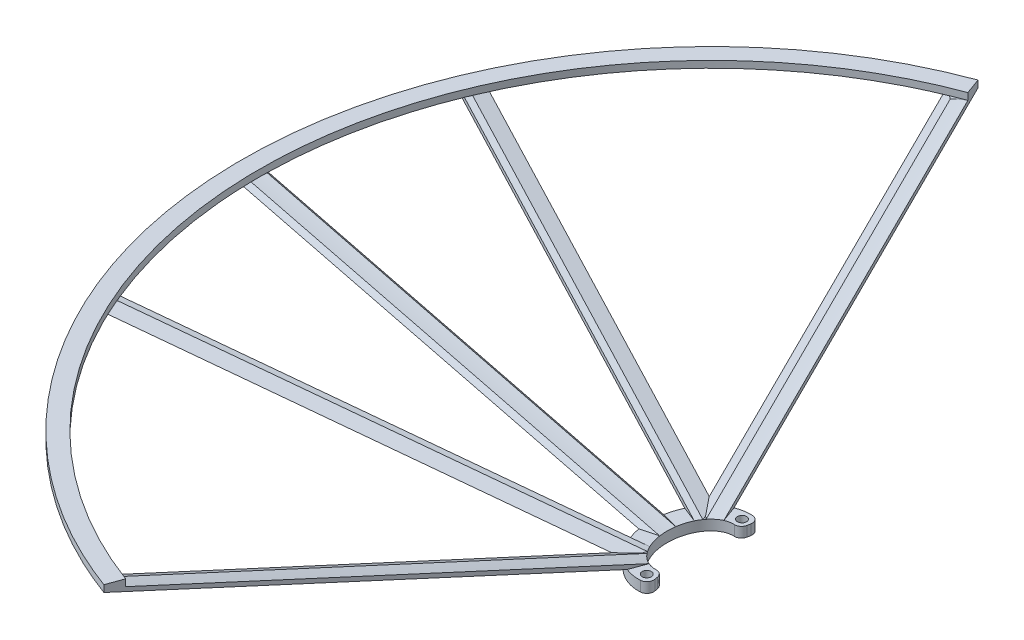
SolidWorks part; units mm, degrees
ref_plane "Front Plane" through (0, 0, 0) normal (0, 0, 1) x (1, 0, 0)
ref_plane "Top Plane" through (0, 0, 0) normal (0, 1, 0) x (1, 0, 0)
ref_plane "Right Plane" through (0, 0, 0) normal (1, 0, 0) x (0, 0, -1)
sketch "Sketch1" plane through (0, 0, 0) normal (0, 1, 0) x (1, 0, 0)
  line L0 (1.9656, -11.1475) -> (2.8392, -16.1017)
  line L1 (1.9656, 11.1475) -> (2.8392, 16.1017)
  line L2 (0, 16.5) -> (0, -16.5) construction
  line L3 (0, 0) -> (2.8392, 16.1017) construction
  line L4 (0, 0) -> (2.8392, -16.1017) construction
  line L5 (-8, 0) -> (8, 0) construction
  ellipse E0 centre (0, 0) end of major axis (0, 11.5) minor radius 8 (1.9656, 11.1475) -> (1.9656, -11.1475) ccw
  ellipse E1 centre (0, 0) end of major axis (0, 16.5) minor radius 13 (2.8392, 16.1017) -> (2.8392, -16.1017) ccw
  dimension "D1" = 8
  dimension "D2" = 5
  dimension "D3" = 10
  dimension "D4" = 10
  dimension "D5" = 5
  dimension "D6" = 23
extrude "Boss-Extrude1" add sketch "Sketch1" along normal blind 3
sketch "Sketch2" plane through (0, 3, 0) normal (0, 1, 0) x (1, 0, 0)
  line L0 (0, -11.5) -> (0, -16.5) construction
  circle A1 centre (0, -14) radius 1.35
  ellipse E1 centre (0, 0) end of major axis (0, 11.5) minor radius 8 (1.9656, 11.1475) -> (1.9656, -11.1475) ccw construction
  ellipse E2 centre (0, 0) end of major axis (0, 16.5) minor radius 13 (2.8392, 16.1017) -> (2.8392, -16.1017) ccw construction
  dimension "D1" = 2.7
extrude "Cut-Extrude1" cut sketch "Sketch2" against normal up to next
mirror "Mirror1" about plane through (0, 0, 0) normal (0, 0, 1) of "Cut-Extrude1"
fillet "Fillet1" radius 2 4 edges at (2.8392, 1.5, 16.1017) (1.9656, 1.5, 11.1475) (1.9656, 1.5, -11.1475) (2.8392, 1.5, -16.1017)
sketch "Sketch4" plane through (0, 3, 0) normal (0, 1, 0) x (1, 0, 0)
  line L0 (-9.0377, -11.8603) -> (-5.2477, -8.6801)
  line L1 (-4.047, -15.6801) -> (-2.3421, -10.9961)
  line L2 (0, -11.5) -> (0, -16.5) construction
  line L3 (-5.2477, -8.6801) -> (-4.047, -15.6801) construction
  line L4 (-7.1427, -10.2702) -> (-3.1946, -13.3381) construction
  ellipse E0 centre (0, 0) end of major axis (0, -16.5) minor radius 13 (-9.0377, -11.8603) -> (-4.047, -15.6801) ccw
  ellipse E1 centre (0, 0) end of major axis (0, 16.5) minor radius 13 (0.6497, 16.4794) -> (0.6497, -16.4794) ccw construction
  ellipse E2 centre (0, 0) end of major axis (0, 11.5) minor radius 8 (0.2561, 11.4941) -> (0.2561, -11.4941) ccw construction
  ellipse E3 centre (0, 0) end of major axis (0, -11.5) minor radius 8 (-5.2477, -8.6801) -> (-2.3421, -10.9961) ccw
  dimension "D1" = 30
  dimension "D2" = 20
  dimension "D3" = 7
  dimension "D4" = 5
ref_plane "Plane1" through (1.4659, 0, 0.5336) normal (0.9397, 0, 0.342) x (0.342, 0, -0.9397)
sketch "Sketch5" plane through (1.4659, 0, 0.5336) normal (0.9397, 0, 0.342) x (0.342, 0, -0.9397)
  line L0 (-16.1186, 3) -> (-136.1186, 33)
  dimension "D1" = 120
  dimension "D2" = 30
sketch "Sketch6" plane through (0, 3, 0) normal (0, 1, 0) x (1, 0, 0)
  line L0 (-8, 0) -> (-13, 0) construction
  line L1 (-7.8311, -2.3506) -> (-12.678, -3.6494)
  line L2 (-10.5, 0) -> (-10.2546, -3) construction
  line L3 (-7.8311, 2.3506) -> (-12.678, 3.6494)
  ellipse E0 centre (0, 0) end of major axis (0, -11.5) minor radius 8 (-7.8311, 2.3506) -> (-7.8311, -2.3506) ccw
  ellipse E1 centre (0, 0) end of major axis (0, 11.5) minor radius 8 (-0.0818, -11.4994) -> (0.2561, -11.4941) ccw construction
  ellipse E2 centre (0, 0) end of major axis (0, 11.5) minor radius 8 (0.2561, 11.4941) -> (0.2561, -11.4941) ccw construction
  ellipse E3 centre (0, 0) end of major axis (0, 16.5) minor radius 13 (0.6497, 16.4794) -> (0.6497, -16.4794) ccw construction
  ellipse E4 centre (0, 0) end of major axis (0, -16.5) minor radius 13 (-12.678, 3.6494) -> (-12.678, -3.6494) ccw
  ellipse E5 centre (0, 0) end of major axis (0, 16.5) minor radius 13 (-0.2926, -16.4958) -> (0.6497, -16.4794) ccw construction
  dimension "D1" = 15
  dimension "D2" = 3
ref_plane "Plane2" through (0, 0, 0) normal (0, 0, -1) x (-1, 0, 0)
sketch "Sketch7" plane through (0, 0, 0) normal (0, 0, -1) x (-1, 0, 0)
  line L0 (10.2546, 3) -> (130.2546, 33)
  line L1 (7.8311, 3) -> (12.678, 3) construction
  dimension "D1" = 30
  dimension "D2" = 120
sweep "Sweep2" add profiles "Sketch6" path "Sketch7"
sweep "Sweep3" add profiles "Sketch4" path "Sketch5"
sketch "Sketch18" plane through (0, 3, 0) normal (0, 1, 0) x (1, 0, 0)
  line L0 (-7.5935, -13.3926) -> (-5.6557, -8.1333)
  line L1 (-6.5745, -6.5522) -> (-11.2001, -8.3767)
  line L2 (-8.8873, -7.4644) -> (-6.6246, -10.763) construction
  line L3 (-6.5745, -6.5522) -> (-7.5935, -13.3926) construction
  ellipse E0 centre (0, 0) end of major axis (0, -11.5) minor radius 8 (-5.6557, -8.1333) -> (-6.5745, -6.5522) cw
  ellipse E1 centre (0, 0) end of major axis (0, 11.5) minor radius 8 (-2.3421, -10.9961) -> (0.2561, -11.4941) ccw construction
  ellipse E2 centre (0, 0) end of major axis (0, 11.5) minor radius 8 (-7.8311, -2.3506) -> (-5.2477, -8.6801) ccw construction
  ellipse E3 centre (0, 0) end of major axis (0, -16.5) minor radius 13 (-7.5935, -13.3926) -> (-11.2001, -8.3767) cw
  ellipse E4 centre (0, 0) end of major axis (0, 16.5) minor radius 13 (-4.047, -15.6801) -> (0.6497, -16.4794) ccw construction
  ellipse E5 centre (0, 0) end of major axis (0, 16.5) minor radius 13 (-12.678, -3.6494) -> (-9.0377, -11.8603) ccw construction
  dimension "D1" = 4
  dimension "D2" = 6.9158
  dimension "D3" = 4.9529
  dimension "D4" = 2.1056
ref_plane "Plane4" through (1.3513, 0, 3.426) normal (-0.3669, 0, -0.9303) x (-0.9303, 0, 0.3669)
sketch "Sketch19" plane through (1.3513, 0, 3.426) normal (-0.3669, 0, -0.9303) x (-0.9303, 0, 0.3669)
  line L0 (8.5201, 3) -> (128.5201, 33)
  dimension "D1" = 30
  dimension "D2" = 120
sweep "Sweep4" add profiles "Sketch18" path "Sketch19"
mirror "Mirror2" about plane through (0, 0, 0) normal (0, 0, 1) of "Sweep3", "Sweep4"
sketch "Sketch8" plane through (0, 33, 0) normal (0, 1, 0) x (1, 0, 0)
  line L0 (-43.3846, 123.7592) -> (-45.0894, 128.4432)
  line L1 (-43.3846, 123.7592) -> (-45.0894, 128.4432) construction
  line L3 (-45.0894, -128.4432) -> (-43.3846, -123.7592)
  line L4 (-45.0894, -128.4432) -> (-43.3846, -123.7592) construction
  ellipse E0 centre (0, 0) end of major axis (0, 136.5285) minor radius 133 (-45.0894, 128.4432) -> (-45.0894, -128.4432) ccw
  ellipse E1 centre (-120, 0) end of major axis (-120, -16.5) minor radius 13 (-132.678, 3.6494) -> (-132.678, -3.6494) ccw construction
  ellipse E2 centre (0, 0) end of major axis (0, 131.5458) minor radius 128 (-43.3846, 123.7592) -> (-43.3846, -123.7592) ccw
  ellipse E3 centre (-120, 0) end of major axis (-120, -11.5) minor radius 8 (-127.8311, 2.3506) -> (-127.8311, -2.3506) ccw construction
  ellipse E4 centre (-41.0424, -112.7631) end of major axis (-41.0424, -124.2631) minor radius 8 (-46.2901, -121.4432) -> (-43.3846, -123.7592) ccw construction
extrude "Boss-Extrude2" add sketch "Sketch8" along normal blind 2
